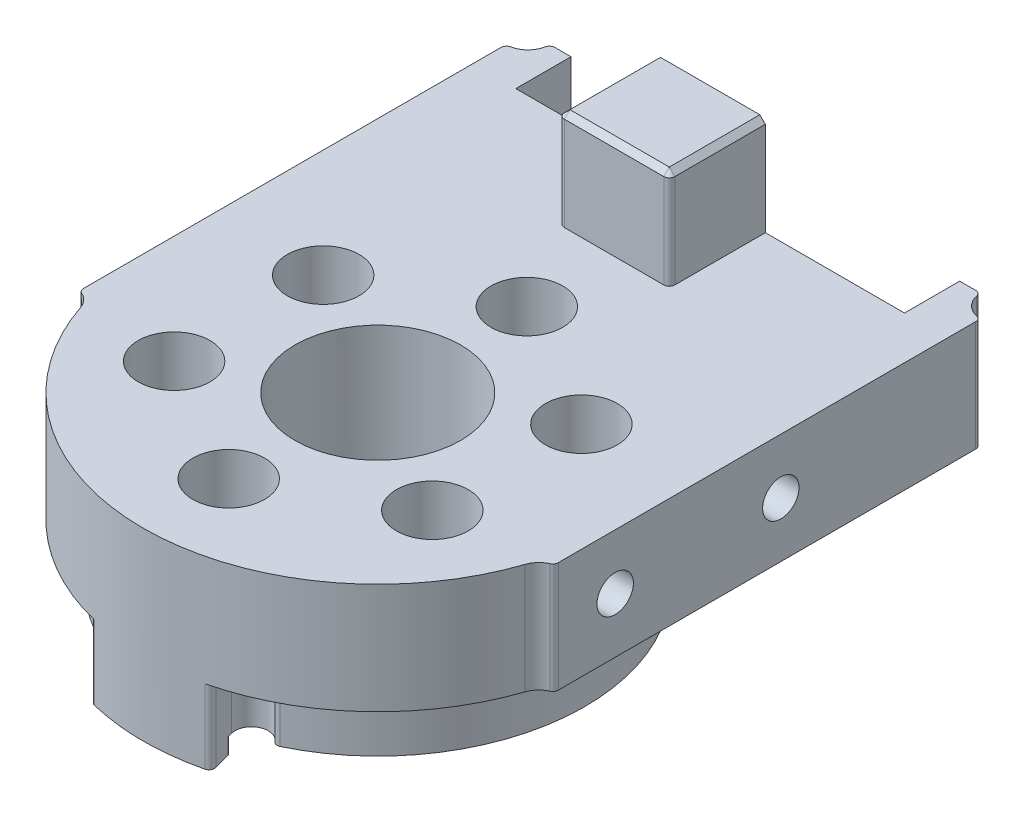
SolidWorks part; units mm, degrees
ref_plane "前视基准面" through (0, 0, 0) normal (0, 0, 1) x (1, 0, 0)
ref_plane "上视基准面" through (0, 0, 0) normal (0, 1, 0) x (1, 0, 0)
ref_plane "右视基准面" through (0, 0, 0) normal (1, 0, 0) x (0, 0, -1)
ref_plane "基准面1" through (0, -51, 0) normal (0, 1, 0) x (1, 0, 0)
sketch "草图1" plane through (0, -51, 0) normal (0, 1, 0) x (1, 0, 0)
  line L0 (21.5, -35.6) -> (-21.5, -35.6)
  arc A0 (20.1363, -36.8891) -> (21.5, -35.6) centre (22.0315, -37.5281) cw
  arc A1 (-21.5, -35.6) -> (-20.1363, -36.8891) centre (-22.0315, -37.5281) cw
  arc A2 (-20.1363, -36.8891) -> (20.1363, -36.8891) centre (0, -30.1) ccw
extrude "凸台-拉伸1" add sketch "草图1" against normal blind 10
sketch "草图2" plane through (0, 0, 35.6) normal (0, 0, -1) x (-1, 0, 0)
  line L0 (21.5, -51) -> (21.5, -61)
  line L1 (21.5, -61) -> (-21.5, -61)
  line L2 (-21.5, -61) -> (-21.5, -51)
  line L3 (-21.5, -51) -> (21.5, -51)
extrude "凸台-拉伸2" add sketch "草图2" along normal blind 24.25
sketch "草图3" plane through (0, -61, 0) normal (0, -1, 0) x (1, 0, 0)
  line L0 (-4.8529, 48.2111) -> (-5.4999, 50.6259)
  line L1 (5.4999, 50.6259) -> (4.8529, 48.2111)
  arc A0 (-5.4999, 50.6259) -> (5.4999, 50.6259) centre (0, 30.1) cw
  arc A1 (4.8529, 48.2111) -> (7.6705, 47.2092) centre (6.3017, 47.8229) ccw
  arc A2 (7.6705, 47.2092) -> (-7.6705, 47.2092) centre (0, 30.1) cw
  arc A3 (-7.6705, 47.2092) -> (-4.8529, 48.2111) centre (-6.3017, 47.8229) ccw
extrude "凸台-拉伸3" add sketch "草图3" along normal blind 6.7
sketch "草图4" plane through (0, -67.7, 0) normal (0, -1, 0) x (1, 0, 0)
  arc A0 (7.6705, 47.2092) -> (4.8529, 48.2111) centre (6.3017, 47.8229) cw
  arc A1 (4.8529, 48.2111) -> (-4.8529, 48.2111) centre (0, 30.1) ccw
  arc A2 (-4.8529, 48.2111) -> (-7.6705, 47.2092) centre (-6.3017, 47.8229) cw
  arc A3 (-7.6705, 47.2092) -> (7.6705, 47.2092) centre (0, 30.1) ccw
extrude "切除-拉伸1" cut sketch "草图4" against normal blind 1.45
sketch "草图5" plane through (0, 0, 11.35) normal (0, 0, -1) x (-1, 0, 0)
  line L0 (21.5, -51) -> (21.5, -61)
  line L1 (21.5, -61) -> (-21.5, -61)
  line L2 (-21.5, -61) -> (-21.5, -51)
  line L3 (-21.5, -51) -> (21.5, -51)
extrude "凸台-拉伸4" add sketch "草图5" along normal blind 16.35
sketch "草图6" plane through (0, 0, -5) normal (0, 0, -1) x (-1, 0, 0)
  line L0 (-17.6, -51) -> (-17.6, -59.1)
  line L1 (-17.6, -59.1) -> (17.6, -59.1)
  line L2 (17.6, -59.1) -> (17.6, -51)
  line L3 (17.6, -51) -> (-17.6, -51)
extrude "切除-拉伸2" cut sketch "草图6" against normal blind 5
sketch "草图7" plane through (0, -51, 0) normal (0, 1, 0) x (-1, 0, 0)
  line L0 (-5, 0) -> (-5, 8.7)
  line L1 (-5, 8.7) -> (5, 8.7)
  line L2 (5, 8.7) -> (5, 0)
  line L3 (5, 0) -> (-5, 0)
extrude "凸台-拉伸5" add sketch "草图7" along normal blind 9
hole_wizard "Ø3.3 (3.3) 直径孔1" positions "草图9" profile "草图8" hole size "Ø3.3" standard "ANSI Metric"
sketch "草图9" plane through (21.5, 0, 0) normal (1, 0, 0) x (0, 0, -1)
  point P0 (-15.1, -56)
  point P1 (-30.1, -56)
sketch "草图8" plane through (21.5, -56, 15.1) normal (0, 1, 0) x (0, 0, -1)
  line L0 (0, 0) -> (0, 9.4914)
  line L1 (0, 9.4914) -> (1.65, 8.5)
  line L2 (1.65, 8.5) -> (1.65, 0)
  line L5 (1.65, 0) -> (0, 0)
  line L10 (0, 9.4914) -> (-1.65, 8.5) construction
  line L11 (0, -6.35) -> (0, 107.95) construction
  dimension "孔直径" = 3.3
  dimension "孔深度" = 8.5
  dimension "导头角度" = 118
hole_wizard "Ø3.3 (3.3) 直径孔2" positions "草图11" profile "草图10" hole size "Ø3.3" standard "ANSI Metric"
sketch "草图11" plane through (-21.5, 0, 0) normal (-1, 0, 0) x (0, 0, 1)
  point P0 (15.1, -56)
  point P1 (30.1, -56)
sketch "草图10" plane through (-21.5, -56, 15.1) normal (0, 1, 0) x (0, 0, 1)
  line L0 (0, 0) -> (0, 9.4914)
  line L1 (0, 9.4914) -> (1.65, 8.5)
  line L2 (1.65, 8.5) -> (1.65, 0)
  line L5 (1.65, 0) -> (0, 0)
  line L10 (0, 9.4914) -> (-1.65, 8.5) construction
  line L11 (0, -6.35) -> (0, 107.95) construction
  dimension "孔直径" = 3.3
  dimension "孔深度" = 8.5
  dimension "导头角度" = 118
hole_wizard "Ø3.3 (3.3) 直径孔3" positions "草图13" profile "草图12" hole size "Ø3.3" standard "ANSI Metric"
sketch "草图13" plane through (0, 0, 0) normal (0, 0, -1) x (-1, 0, 0)
  point P0 (-9.5, -55)
  point P1 (9.5, -55)
sketch "草图12" plane through (9.5, -55, 0) normal (1, 0, 0) x (0, 1, 0)
  line L0 (0, 0) -> (0, 9.9914)
  line L1 (0, 9.9914) -> (1.65, 9)
  line L2 (1.65, 9) -> (1.65, 0)
  line L5 (1.65, 0) -> (0, 0)
  line L10 (0, 9.9914) -> (-1.65, 9) construction
  line L11 (0, -6.35) -> (0, 107.95) construction
  dimension "孔直径" = 3.3
  dimension "孔深度" = 9
  dimension "导头角度" = 118
hole_wizard "Ø15.0 (15) 直径孔1" positions "草图15" profile "草图14" hole size "Ø15.0" standard "ANSI Metric"
sketch "草图15" plane through (0, -66.25, 0) normal (0, -1, 0) x (1, 0, 0)
  point P0 (0, 30.1)
  point P1 (0, 30.1)
sketch "草图14" plane through (0, -66.25, 30.1) normal (1, 0, 0) x (0, 0, -1)
  line L0 (0, 0) -> (0, 24.25)
  line L1 (0, 24.25) -> (7.5, 24.25)
  line L2 (7.5, 24.25) -> (7.5, 0)
  line L5 (7.5, 0) -> (0, 0)
  line L11 (0, -6.35) -> (0, 107.95) construction
  dimension "通孔孔直径" = 15
  dimension "通孔孔深度" = 24.25
hole_wizard "M3 六角头机械螺钉的柱形沉头孔1" positions "草图17" profile "草图16" counterbore size "M3" standard "ANSI Metric"
sketch "草图17" plane through (0, -51, 0) normal (0, 1, 0) x (1, 0, 0)
  point P0 (0, -43.6)
  point P1 (-11.6913, -36.85)
  point P2 (-11.6913, -23.35)
  point P3 (0, -16.6)
  point P4 (11.6913, -23.35)
  point P5 (11.6913, -36.85)
sketch "草图16" plane through (0, -51, 43.6) normal (1, 0, 0) x (0, 0, 1)
  line L0 (0, 0) -> (0, 16.7)
  line L1 (0, 16.7) -> (1.7, 16.7)
  line L3 (1.7, 16.7) -> (1.7, 4.75)
  line L4 (1.7, 4.75) -> (3.25, 4.75)
  line L5 (3.25, 4.75) -> (3.25, 0)
  line L7 (3.25, 0) -> (0, 0)
  line L11 (0, -6.35) -> (0, 107.95) construction
  dimension "通孔孔直径" = 3.4
  dimension "通孔孔深度" = 16.7
  dimension "柱形沉头孔直径" = 6.5
  dimension "柱形沉头孔深度" = 4.75
hole_wizard "Ø4.0 (4) 直径孔1" positions "草图19" profile "草图18" hole size "Ø4.0" standard "ANSI Metric"
sketch "草图19" plane through (0, -51, 0) normal (0, 1, 0) x (1, 0, 0)
  point P0 (21.5, 5)
  point P1 (-21.5, 5)
sketch "草图18" plane through (21.5, -51, -5) normal (1, 0, 0) x (0, 0, 1)
  line L0 (0, 0) -> (0, 16.7)
  line L1 (0, 16.7) -> (2, 16.7)
  line L2 (2, 16.7) -> (2, 0)
  line L5 (2, 0) -> (0, 0)
  line L11 (0, -6.35) -> (0, 107.95) construction
  dimension "通孔孔直径" = 4
  dimension "通孔孔深度" = 16.7
fillet "圆角1" radius 0.5 14 edges at (19.5, -56, -5) (-21.5, -56, -3) (-21.5, -56, 35.6) (-4.8529, -66.975, 48.2111) (21.5, -56, -3) (5.4999, -64.35, 50.6259) (4.8529, -66.975, 48.2111) (-5.4999, -64.35, 50.6259) (21.5, -56, 35.6) (7.6705, -63.625, 47.2092) (-7.6705, -63.625, 47.2092) (-19.5, -56, -5) (5, -46.5, 8.7) (-5, -46.5, 8.7)
chamfer "倒角1" distance 0.5 angle 45 5 edges at (-5, -42, 4.1) (-4.8536, -42, 8.5536) (0, -42, 8.7) (4.8536, -42, 8.5536) (5, -42, 4.1)
fillet "圆角2" radius 2 2 edges at (17.6, -59.1, -2.5) (-17.6, -59.1, -2.5)
